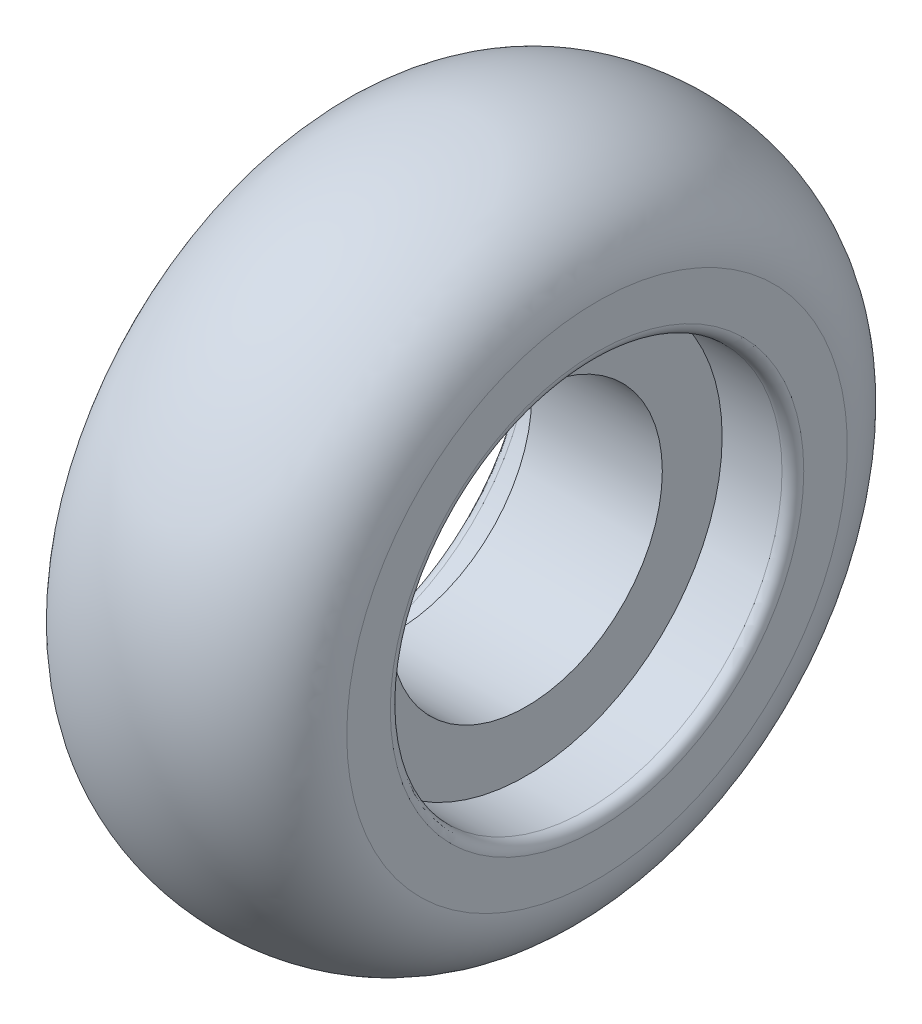
SolidWorks part; units mm, degrees
material "Guma"
ref_plane "Płaszczyzna przednia" through (0, 0, 0) normal (0, 0, 1) x (1, 0, 0)
ref_plane "Płaszczyzna górna" through (0, 0, 0) normal (0, 1, 0) x (1, 0, 0)
ref_plane "Płaszczyzna prawa" through (0, 0, 0) normal (1, 0, 0) x (0, 0, -1)
sketch "Szkic1" plane through (0, 0, 0) normal (0, 0, 1) x (1, 0, 0)
  line L0 (0, 0) -> (14.4807, 0) construction
  line L1 (0, 0) -> (0, 36.4941) construction
  line L2 (-6, 12.5) -> (6, 12.5)
  line L3 (6, 12.5) -> (6, 18)
  line L4 (6, 18) -> (11.5, 18)
  line L5 (12.5, 19) -> (12.5, 23)
  line L6 (-12.5, 19) -> (-12.5, 23)
  line L7 (-6, 18) -> (-11.5, 18)
  line L8 (-6, 12.5) -> (-6, 18)
  arc A0 (11.5, 18) -> (12.5, 19) centre (11.5, 19) ccw
  arc A1 (-11.5, 18) -> (-12.5, 19) centre (-11.5, 19) cw
  ellipse E0 centre (0, 23) end of major axis (12.5, 23) minor radius 8.5 (12.5, 23) -> (-12.5, 23) ccw
  point P18 (0, 12.5)
  dimension "D6" = 1
  dimension "D1" = 25
  dimension "D2" = 36
  dimension "D3" = 12
  dimension "D4" = 25
  dimension "D5" = 46
  dimension "D7" = 63
revolve "Obrót1" add sketch "Szkic1" angle 360 about L0
